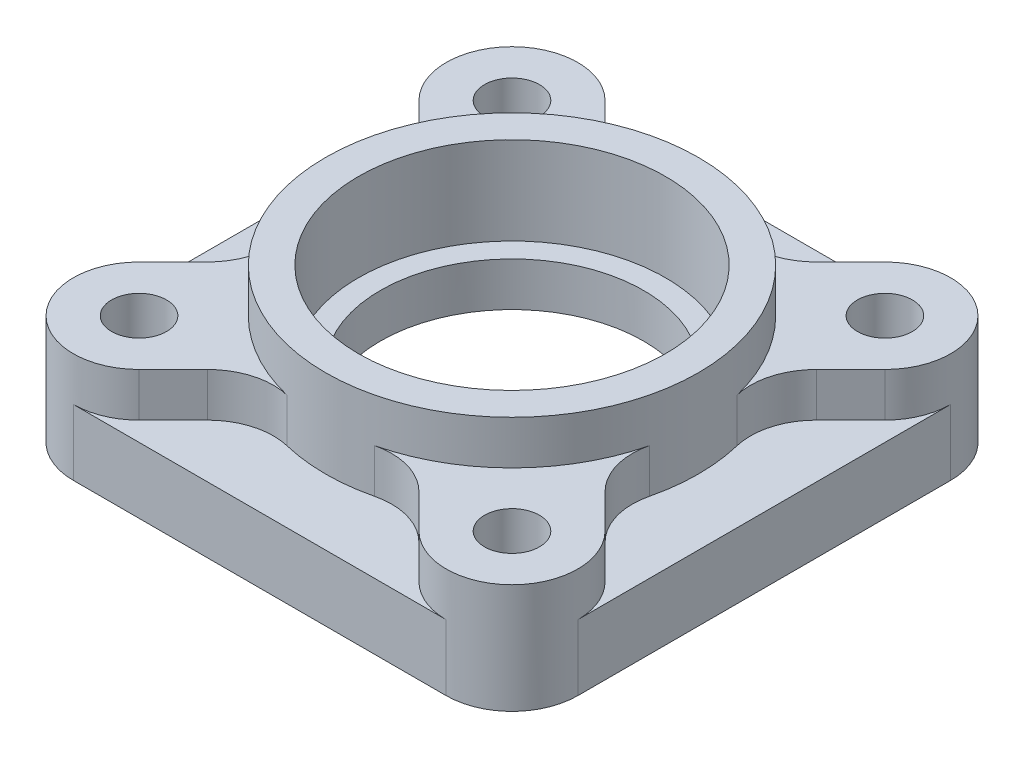
SolidWorks part; units mm, degrees
ref_plane "Front Plane" through (0, 0, 0) normal (0, 0, 1) x (1, 0, 0)
ref_plane "Top Plane" through (0, 0, 0) normal (0, 1, 0) x (1, 0, 0)
ref_plane "Right Plane" through (0, 0, 0) normal (1, 0, 0) x (0, 0, -1)
sketch "Sketch1" plane through (0, 0, 0) normal (0, 1, 0) x (1, 0, 0)
  line L1 (-26.9875, -36.5125) -> (26.9875, -36.5125)
  line L2 (-36.5125, -26.9875) -> (-36.5125, 26.9875)
  line L3 (-26.9875, 36.5125) -> (26.9875, 36.5125)
  line L4 (36.5125, -26.9875) -> (36.5125, 26.9875)
  line L5 (-36.5125, -36.5125) -> (36.5125, 36.5125) construction
  line L6 (-36.5125, 36.5125) -> (36.5125, -36.5125) construction
  arc A0 (-26.9875, -36.5125) -> (-36.5125, -26.9875) centre (-26.9875, -26.9875) cw
  arc A1 (26.9875, -36.5125) -> (36.5125, -26.9875) centre (26.9875, -26.9875) ccw
  arc A2 (36.5125, 26.9875) -> (26.9875, 36.5125) centre (26.9875, 26.9875) ccw
  arc A3 (-36.5125, 26.9875) -> (-26.9875, 36.5125) centre (-26.9875, 26.9875) cw
  point P0 (0, 0)
  dimension "D3" = 9.525
  dimension "D1" = 73.025
  dimension "D2" = 73.025
extrude "Boss-Extrude1" add sketch "Sketch1" along normal blind 9.525
sketch "Sketch2" plane through (0, 0, 0) normal (0, -1, 0) x (1, 0, 0)
  circle A0 centre (0, 0) radius 26.9875
  dimension "D1" = 53.975
extrude "Cut-Extrude1" cut sketch "Sketch2" against normal blind 3.175
sketch "Sketch3" plane through (0, 9.525, 0) normal (0, 1, 0) x (1, 0, 0)
  circle A0 centre (0, 0) radius 26.9875
  dimension "D1" = 53.975
extrude "Boss-Extrude2" add sketch "Sketch3" along normal blind 12.7
sketch "Sketch4" plane through (0, 22.225, 0) normal (0, 1, 0) x (1, 0, 0)
  circle A0 centre (0, 0) radius 22.225
  dimension "D1" = 44.45
extrude "Cut-Extrude2" cut sketch "Sketch4" against normal blind 12.7
sketch "Sketch5" plane through (0, 9.525, 0) normal (0, 1, 0) x (1, 0, 0)
  circle A0 centre (0, 0) radius 19.05
  dimension "D1" = 38.1
extrude "Cut-Extrude3" cut sketch "Sketch5" against normal through all
sketch "Sketch6" plane through (0, 9.525, 0) normal (0, 1, 0) x (1, 0, 0)
  circle A0 centre (0, 0) radius 31.75
  point P5 (0, 31.75)
  dimension "D1" = 63.5
hole_wizard "3/16 (0.1875) Diameter Hole1" positions "Sketch6" profile "Sketch7" hole size "3/16" standard "ANSI Inch"
sketch "Sketch7" plane through (0, 9.525, -31.75) normal (1, 0, 0) x (0, 0, 1)
  line L0 (0, 0) -> (0, 6.1933)
  line L1 (0, 6.1933) -> (2.3812, 4.7625)
  line L2 (2.3812, 4.7625) -> (2.3812, 0)
  line L5 (2.3812, 0) -> (0, 0)
  line L10 (0, 6.1933) -> (-2.3813, 4.7625) construction
  line L11 (0, -6.35) -> (0, 107.95) construction
  dimension "Hole Dia." = 4.7625
  dimension "Hole Depth" = 4.7625
  dimension "Drill Angle" = 118
sketch "Sketch9" plane through (0, 9.525, 0) normal (0, 1, 0) x (1, 0, 0)
  line L0 (0, 0) -> (0, 13.4704) construction
  line L1 (26.9875, 36.5125) -> (-26.9875, 36.5125) construction
  line L2 (0, 0) -> (20.2523, 20.2523) construction
  line L3 (24.5902, 11.1198) -> (33.7227, 20.2523)
  line L4 (11.1198, 24.5902) -> (20.2523, 33.7227)
  line L5 (6.7352, -6.7352) -> (43.2477, 29.7773) construction
  line L6 (-6.7352, 6.7352) -> (29.7773, 43.2477) construction
  line L7 (0, 26.9875) -> (0, 36.5125) construction
  line L8 (33.7227, 33.7227) -> (36.5125, 36.5125) construction
  line L9 (0, 0) -> (36.5125, 36.5125) construction
  line L10 (24.5902, -11.1198) -> (33.7227, -20.2523)
  line L11 (11.1198, -24.5902) -> (20.2523, -33.7227)
  line L12 (-11.1198, -24.5902) -> (-20.2523, -33.7227)
  line L13 (-24.5902, -11.1198) -> (-33.7227, -20.2523)
  line L14 (-24.5902, 11.1198) -> (-33.7227, 20.2523)
  line L15 (-11.1198, 24.5902) -> (-20.2523, 33.7227)
  arc A0 (33.7227, 20.2523) -> (20.2523, 33.7227) centre (26.9875, 26.9875) ccw
  circle A2 centre (0, 0) radius 26.9875
  arc A3 (20.2523, -33.7227) -> (33.7227, -20.2523) centre (26.9875, -26.9875) ccw
  arc A4 (-33.7227, -20.2523) -> (-20.2523, -33.7227) centre (-26.9875, -26.9875) ccw
  arc A5 (-20.2523, 33.7227) -> (-33.7227, 20.2523) centre (-26.9875, 26.9875) ccw
  point P39 (0, 0)
  circle M7 centre (0, 0) radius 26.9875
  arc M8 (-36.5125, -26.9875) -> (-26.9875, -36.5125) centre (-26.9875, -26.9875) ccw
  arc M10 (26.9875, -36.5125) -> (36.5125, -26.9875) centre (26.9875, -26.9875) ccw
  arc M12 (36.5125, 26.9875) -> (26.9875, 36.5125) centre (26.9875, 26.9875) ccw
  arc M14 (-26.9875, 36.5125) -> (-36.5125, 26.9875) centre (-26.9875, 26.9875) ccw
  dimension "D4" = 19.05
  dimension "D1" = 45
  dimension "D2" = 9.525
  dimension "D3" = 9.525
  dimension "D5" = 4
extrude "Boss-Extrude3" add sketch "Sketch9" along normal blind 6.35 contours L15 A5 L14 M14 M7 | L3 A0 L4 M12 M7 | A3 L10 L11 M10 M7 | A4 L12 L13 M8 M7
fillet "Fillet1" radius 9.525 8 edges at (24.5902, 12.7, 11.1198) (11.1198, 12.7, 24.5902) (-11.1198, 12.7, 24.5902) (-24.5902, 12.7, 11.1198) (-24.5902, 12.7, -11.1198) (-11.1198, 12.7, -24.5902) (11.1198, 12.7, -24.5902) (24.5902, 12.7, -11.1198)
sketch "Sketch10" plane through (0, 15.875, 0) normal (0, 1, 0) x (1, 0, 0)
  line L0 (-28.7609, 15.2905) -> (-33.7227, 20.2523) construction
  line L1 (-36.5125, 26.9875) -> (-36.5125, -26.9875) construction
  line L2 (26.9875, 36.5125) -> (-26.9875, 36.5125) construction
  circle A0 centre (-26.9875, 26.9875) radius 3.9751
  arc A1 (-20.2523, 33.7227) -> (-33.7227, 20.2523) centre (-26.9875, 26.9875) ccw construction
  circle A2 centre (26.9875, 26.9875) radius 3.9751
  circle A3 centre (26.9875, -26.9875) radius 3.9751
  circle A4 centre (-26.9875, -26.9875) radius 3.9751
  point P16 (0, 0)
  point P18 (-68.2975, 25.8415)
  dimension "D1" = 9.525
  dimension "D2" = 0
  dimension "D4" = 7.9502
  dimension "D5" = 90
  dimension "D6" = 9.525
  dimension "D3" = 4
extrude "Cut-Extrude4" cut sketch "Sketch10" against normal through all
